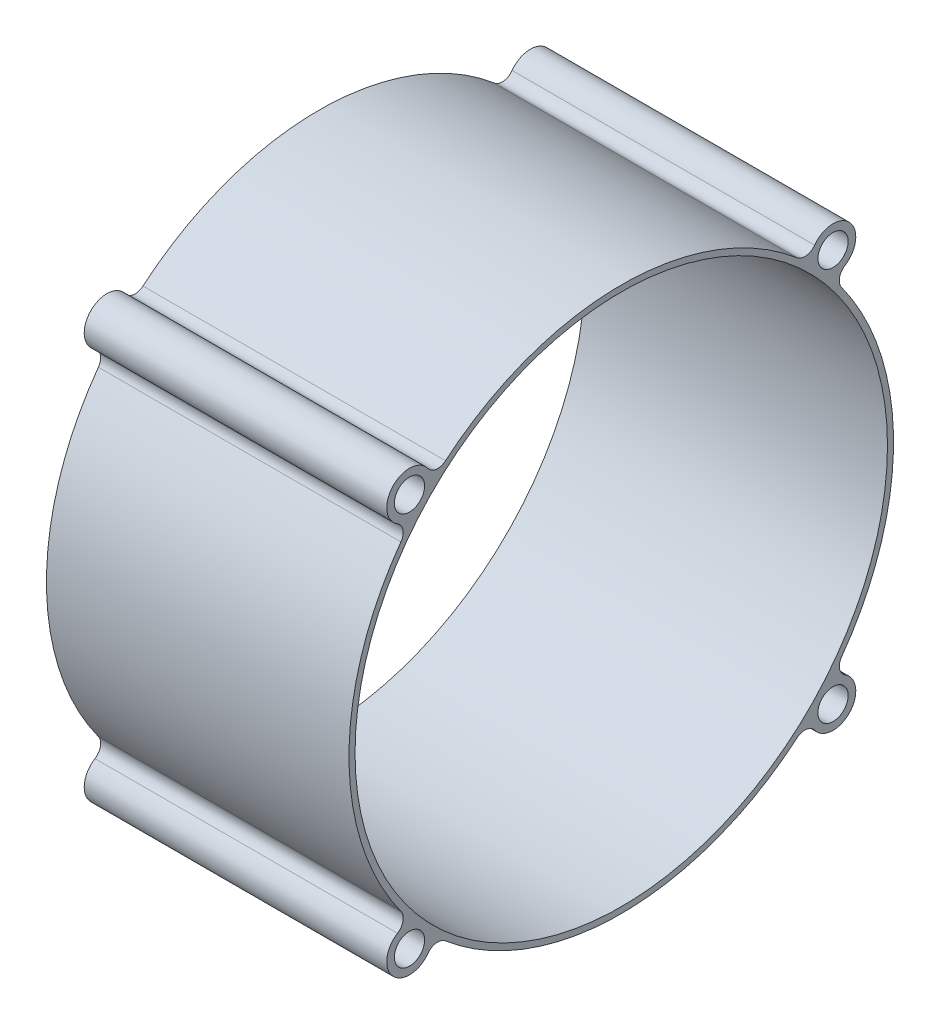
SolidWorks part; units mm, degrees
ref_plane "Front Plane" through (0, 0, 0) normal (0, 0, 1) x (1, 0, 0)
ref_plane "Top Plane" through (0, 0, 0) normal (0, 1, 0) x (1, 0, 0)
ref_plane "Right Plane" through (0, 0, 0) normal (1, 0, 0) x (0, 0, -1)
sketch "Sketch1" plane through (0, 0, 0) normal (1, 0, 0) x (0, 0, -1)
  line L0 (0, 65.0519) -> (0, -70.652)
  line L1 (-77.0603, 0) -> (114.1262, 0)
  circle A2 centre (0, 0) radius 45
  circle A4 centre (-35, -32.5) radius 2.5
  circle A6 centre (35, -32.5) radius 2.5
  circle A7 centre (-35, 32.5) radius 2.5
  circle A8 centre (35, 32.5) radius 2.5
  circle A9 centre (0, 0) radius 44
  circle A10 centre (-35, 32.5) radius 3.7624
  circle A11 centre (-35, -32.5) radius 3.7624
  circle A12 centre (35, -32.5) radius 3.7624
  circle A13 centre (35, 32.5) radius 3.7624
  dimension "D1" = 90
  dimension "D3" = 5
  dimension "D4" = 88
  dimension "D5" = 32.5
  dimension "D7" = 35
extrude "Boss-Extrude5" add sketch "Sketch1" along normal blind 50 contours A11 A9 L1 A2 | A10 A2 L1 A9 | A10 A9 L0 A2 | A2 A11 A4 | A2 A10 A7 | A2 A13 A8 | A2 A12 A6
sketch "Sketch2" plane through (50, 0, 0) normal (1, 0, 0) x (0, 0, -1)
  circle A0 centre (35, -32.5) radius 2.5
  dimension "D1" = 5
extrude "Cut-Extrude1" cut sketch "Sketch2" against normal blind 50
fillet "Fillet1" radius 2 8 edges at (25, -28.7576, -34.6121) (25, -32.39, -31.2392) (25, -32.39, 31.2392) (25, -28.7576, 34.6121) (25, 28.7576, 34.6121) (25, 32.39, 31.2392) (25, 32.39, -31.2392) (25, 28.7576, -34.6121)
